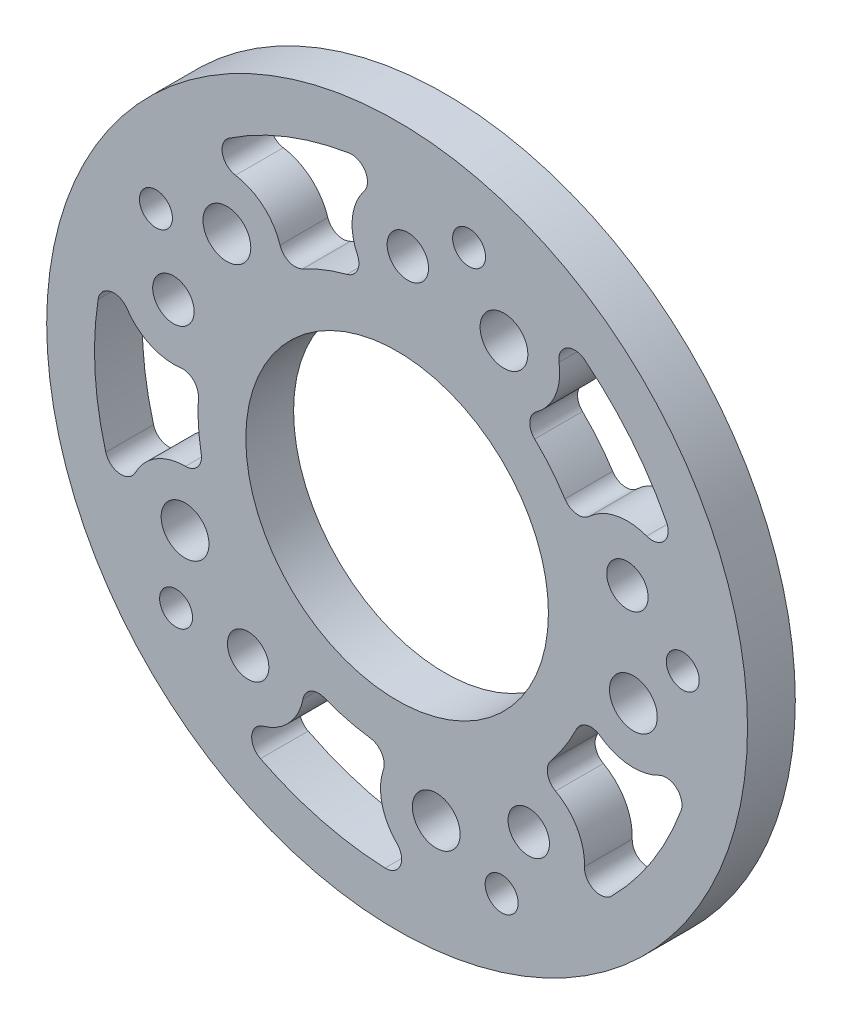
SolidWorks part; units mm, degrees
ref_plane "前视基准面" through (0, 0, 0) normal (0, 0, 1) x (1, 0, 0)
ref_plane "上视基准面" through (0, 0, 0) normal (0, 1, 0) x (1, 0, 0)
ref_plane "右视基准面" through (0, 0, 0) normal (1, 0, 0) x (0, 0, -1)
sketch "草图1" plane through (0, 0, 0) normal (0, 0, 1) x (1, 0, 0)
  line L0 (0.6719, 14.9849) -> (0, 0) construction
  line L1 (0, 0) -> (11.9604, 23.9182) construction
  line L2 (0, 0) -> (-9.0803, 23.1314) construction
  line L3 (0, 0) -> (-17.5585, 17.2954) construction
  line L4 (0, 0) -> (-23.5177, 15.0214) construction
  circle A0 centre (0, 0) radius 9.5
  circle A1 centre (0, 0) radius 22
  circle A2 centre (8.2643, -12.518) radius 1.3
  circle A3 centre (0, 0) radius 15 construction
  circle A9 centre (-9.3515, -11.7281) radius 1.3
  circle A11 centre (-14.0439, 5.2696) radius 1.3
  circle A13 centre (0.6719, 14.9849) radius 1.3
  circle A15 centre (14.4592, 3.9916) radius 1.3
  circle A17 centre (14.0439, -5.2696) radius 1.3 [skipped]
  circle A18 centre (-0.6719, -14.9849) radius 1.3 [skipped]
  circle A19 centre (-14.4592, -3.9916) radius 1.3 [skipped]
  circle A20 centre (-8.2643, 12.518) radius 1.3 [skipped]
  circle A21 centre (9.3515, 11.7281) radius 1.3 [skipped]
  circle A22 centre (6.7088, 13.4161) radius 1.5
  circle A23 centre (14.8326, -2.2346) radius 1.5
  circle A24 centre (2.4583, -14.7972) radius 1.5
  circle A25 centre (-13.3133, -6.9106) radius 1.5
  circle A26 centre (-10.6864, 10.5262) radius 1.5
  circle A27 centre (-14.0439, 5.2696) radius 3.5 construction
  circle A28 centre (-10.6864, 10.5262) radius 3.5 construction
  circle A29 centre (0, 0) radius 19 construction
  circle A30 centre (-9.9916, 14.9723) radius 1 construction
  circle A31 centre (0, 0) radius 12.5 construction
  circle A33 centre (-6.3974, 11.888) radius 1 construction
  circle A76 centre (-15.14, 9.6703) radius 1.0352
  arc A77 (-5.9235, 11.0074) -> (-7.3505, 11.5854) centre (-6.3974, 11.888) cw
  arc A78 (-10.146, 13.9843) -> (-10.5467, 15.8041) centre (-9.9916, 14.9723) cw
  arc A79 (-7.3505, 11.5854) -> (-10.146, 13.9843) centre (-10.6864, 10.5262) ccw
  arc A80 (-2.0766, 17.1519) -> (-3.0209, 18.7583) centre (-2.8619, 17.771) ccw
  arc A81 (-3.1464, 12.0975) -> (-2.4936, 13.4919) centre (-3.3981, 13.0653) ccw
  arc A82 (-2.4936, 13.4919) -> (-2.0766, 17.1519) centre (0.6719, 14.9849) cw
  arc A83 (-3.0209, 18.7583) -> (-10.5467, 15.8041) centre (0, 0) ccw
  arc A84 (-3.1464, 12.0975) -> (-5.9235, 11.0074) centre (0, 0) ccw
  arc A85 (10.5331, 6.7307) -> (8.6382, 9.035) centre (0, 0) ccw
  arc A86 (16.9067, 8.6696) -> (11.7715, 14.9142) centre (0, 0) ccw
  arc A87 (12.061, 6.5408) -> (15.6707, 7.2752) centre (14.4592, 3.9916) cw
  arc A88 (8.7469, 10.5708) -> (10.1645, 13.9708) centre (6.7088, 13.4161) ccw
  arc A89 (15.6707, 7.2752) -> (16.9067, 8.6696) centre (16.0169, 8.2133) ccw
  arc A90 (10.1645, 13.9708) -> (11.7715, 14.9142) centre (11.1519, 14.1292) cw
  arc A91 (10.5331, 6.7307) -> (12.061, 6.5408) centre (11.3758, 7.2692) ccw
  arc A92 (8.6382, 9.035) -> (8.7469, 10.5708) centre (9.3292, 9.7578) cw
  arc A93 (9.6562, -7.9377) -> (11.2622, -5.4234) centre (0, 0) ccw
  arc A94 (13.4698, -13.4002) -> (17.8218, -6.5866) centre (0, 0) ccw
  arc A95 (9.9477, -9.4495) -> (11.7616, -12.6556) centre (8.2643, -12.518) cw
  arc A96 (12.7564, -5.0523) -> (16.428, -5.3498) centre (14.8326, -2.2346) ccw
  arc A97 (11.7616, -12.6556) -> (13.4698, -13.4002) centre (12.7608, -12.6949) ccw
  arc A98 (16.428, -5.3498) -> (17.8218, -6.5866) centre (16.8838, -6.2399) cw
  arc A99 (9.6562, -7.9377) -> (9.9477, -9.4495) centre (10.4287, -8.5727) ccw
  arc A100 (11.2622, -5.4234) -> (12.7564, -5.0523) centre (12.1631, -5.8573) cw
  arc A101 (-4.5653, -11.6365) -> (-1.6778, -12.3869) centre (0, 0) ccw
  arc A102 (-8.5819, -16.9514) -> (-0.757, -18.9849) centre (0, 0) ccw
  arc A103 (-5.9129, -12.3809) -> (-8.4017, -15.0968) centre (-9.3515, -11.7281) cw
  arc A104 (-0.863, -13.6933) -> (-0.0115, -17.2771) centre (2.4583, -14.7972) ccw
  arc A105 (-8.4017, -15.0968) -> (-8.5819, -16.9514) centre (-8.1303, -16.0592) ccw
  arc A106 (-0.0115, -17.2771) -> (-0.757, -18.9849) centre (-0.7171, -17.9857) cw
  arc A107 (-4.5653, -11.6365) -> (-5.9129, -12.3809) centre (-4.9305, -12.5674) ccw
  arc A108 (-1.6778, -12.3869) -> (-0.863, -13.6933) centre (-1.812, -13.3778) cw
  arc A109 (-12.4777, 0.746) -> (-12.2991, -2.2321) centre (0, 0) ccw
  arc A110 (-18.7737, 2.9236) -> (-18.2896, -5.1467) centre (0, 0) ccw
  arc A111 (-13.6022, 1.7976) -> (-16.9541, 3.3253) centre (-14.0439, 5.2696) cw
  arc A112 (-13.2898, -3.4106) -> (-16.4351, -5.328) centre (-13.3133, -6.9106) ccw
  arc A113 (-16.9541, 3.3253) -> (-18.7737, 2.9236) centre (-17.7856, 2.7698) ccw
  arc A114 (-16.4351, -5.328) -> (-18.2896, -5.1467) centre (-17.327, -4.8759) cw
  arc A115 (-12.4777, 0.746) -> (-13.6022, 1.7976) centre (-13.4759, 0.8056) ccw
  arc A116 (-12.2991, -2.2321) -> (-13.2898, -3.4106) centre (-13.283, -2.4107) cw
  circle A117 centre (4.5185, 17.3873) radius 1.0352
  circle A118 centre (17.9326, 1.0756) radius 1.0352
  circle A119 centre (6.5645, -16.7226) radius 1.0352
  circle A120 centre (-13.8756, -11.4107) radius 1.0352
  dimension "D1" = 19
  dimension "D2" = 2.6
  dimension "D3" = 30
  dimension "D4" = 44
  dimension "D6" = 24
  dimension "D7" = 5
  dimension "D8" = 48
  dimension "D9" = 12
  dimension "D10" = 24
  dimension "D11" = 5
  dimension "D5" = 10
extrude "凸台-拉伸1" add sketch "草图1" along normal blind 3
